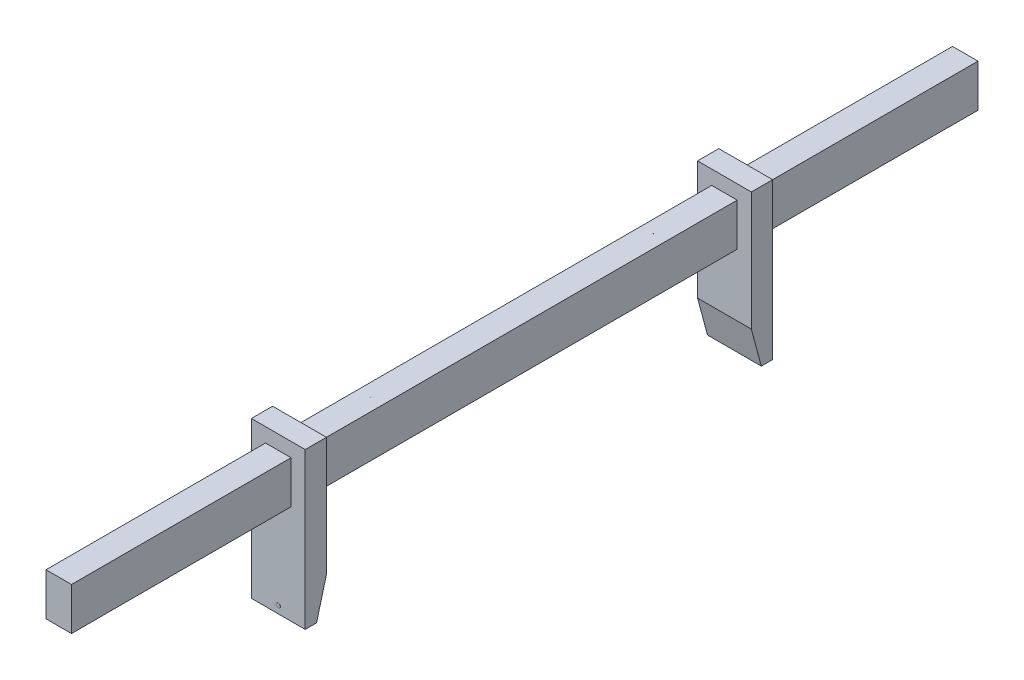
SolidWorks part; units mm, degrees
ref_plane "前视基准面" through (0, 0, 0) normal (0, 0, 1) x (1, 0, 0)
ref_plane "上视基准面" through (0, 0, 0) normal (0, 1, 0) x (1, 0, 0)
ref_plane "右视基准面" through (0, 0, 0) normal (1, 0, 0) x (0, 0, -1)
sketch "草图1" plane through (0, 0, 0) normal (0, 0, 1) x (1, 0, 0)
  line L1 (-9, -15) -> (9, -15)
  line L2 (-9, -15) -> (-9, 15)
  line L3 (-9, 15) -> (9, 15)
  line L4 (9, -15) -> (9, 15)
  line L5 (-9, -15) -> (9, 15) construction
  line L6 (-9, 15) -> (9, -15) construction
  point P0 (0, 0)
  dimension "D1" = 30
  dimension "D2" = 18
extrude "凸台-拉伸1" add sketch "草图1" along normal mid plane 600
sketch "草图3" plane through (0, 0, 300) normal (0, 0, 1) x (1, 0, 0)
  line L0 (-9, -15) -> (-9, -15.05)
  line L1 (-9, -15.05) -> (9, -15.05)
  line L2 (9, -15.05) -> (9, -15)
  line L3 (-9, -15) -> (-9, 15)
  line L4 (-9, 15) -> (9, 15)
  line L5 (9, 15) -> (9, -15)
  dimension "D1" = 0.05
extrude "凸台-拉伸2" add sketch "草图3" along normal blind 20
mirror "镜向1" about plane through (0, 0, 0) normal (0, 0, 1) of "凸台-拉伸2"
ref_plane "基准面1" through (0, 0, 165) normal (0, 0, 1) x (1, 0, 0)
sketch "草图4" plane through (0, 0, 165) normal (0, 0, 1) x (1, 0, 0)
  line L0 (-19, 25) -> (19, 25)
  line L1 (19, 25) -> (19, -80)
  line L2 (19, -80) -> (-19, -80)
  line L3 (-19, -80) -> (-19, 25)
  line L4 (9, -15.05) -> (9, 15) construction
  line L5 (-9, 15) -> (-9, -15.05) construction
  line L7 (9, 15) -> (-9, 15) construction
  dimension "D1" = 80
  dimension "D2" = 10
  dimension "D3" = 10
  dimension "D4" = 10
ref_plane "基准面2" through (19, 0, 0) normal (1, 0, 0) x (0, 0, -1)
sketch "草图5" plane through (19, 0, 0) normal (1, 0, 0) x (0, 0, -1)
  line L0 (-165, 25) -> (-165, -85)
  line L1 (-165, 20.9) -> (-165, -20.9) construction
  line L2 (-165, -85) -> (-157, -85)
  line L3 (-157, -85) -> (-150, -58.8756)
  line L4 (-150, -58.8756) -> (-150, 25)
  line L5 (-150, 25) -> (-165, 25)
  line L6 (-361.5632, 0) -> (45.9505, 0) construction
  line L8 (-320, 15) -> (320, 15) construction
  point P8 (-161, -85)
  dimension "D1" = 85
  dimension "D2" = 10
  dimension "D3" = 15
  dimension "D4" = 8
  dimension "D5" = 15
extrude "凸台-拉伸3" add sketch "草图5" against normal blind 38
mirror "镜向2" about plane through (0, 0, 0) normal (0, 0, 1) of "凸台-拉伸3"
sketch "草图6" plane through (0, 15, 0) normal (0, 1, 0) x (1, 0, 0)
  circle A0 centre (0, 100) radius 0.25
  dimension "D1" = 0.5
  dimension "D2" = 100
extrude "凸台-拉伸4" add sketch "草图6" along normal blind 0.05
mirror "镜向3" about plane through (0, 0, 0) normal (0, 0, 1) of "凸台-拉伸4"
sketch "草图8" plane through (0, -26.505, 165) normal (0, 0, 1) x (1, 0, 0)
  circle A0 centre (0, -53.3318) radius 1.5
  dimension "D1" = 3
extrude "凸台-拉伸5" add sketch "草图8" along normal blind 0.1
mirror "镜向4" about plane through (0, 0, 0) normal (0, 0, 1) of "凸台-拉伸5"
